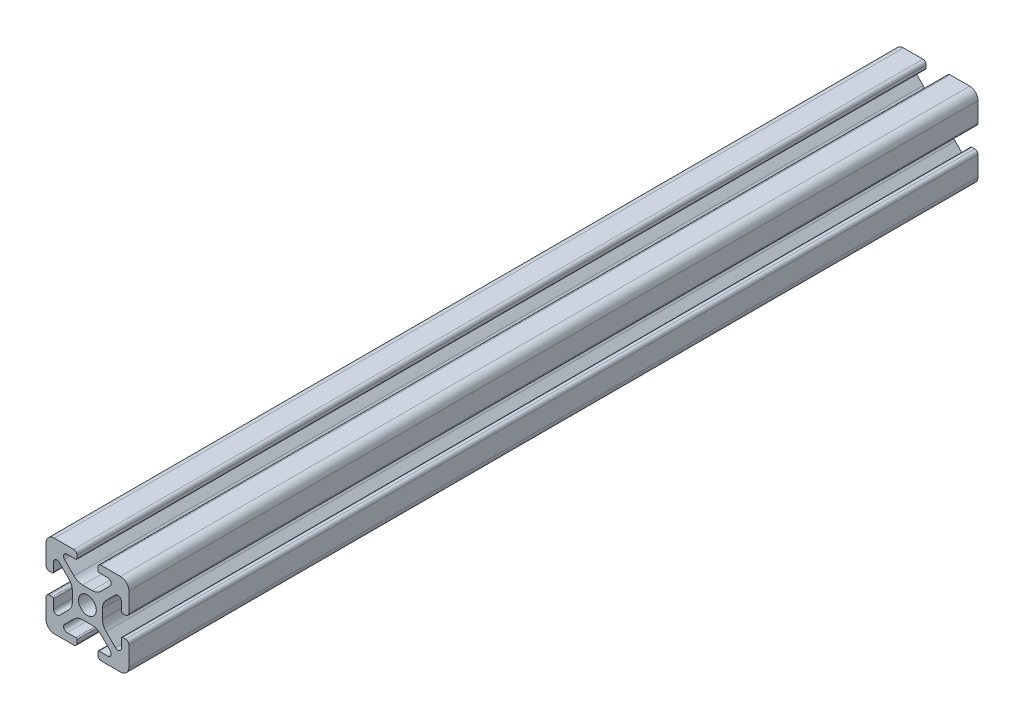
SolidWorks part; units mm, degrees
ref_plane "Front Plane" through (0, 0, 0) normal (0, 0, 1) x (1, 0, 0)
ref_plane "Top Plane" through (0, 0, 0) normal (0, 1, 0) x (1, 0, 0)
ref_plane "Right Plane" through (0, 0, 0) normal (1, 0, 0) x (0, 0, -1)
sketch "Sketch1" plane through (0, 0, 0) normal (0, 0, 1) x (1, 0, 0)
  line L2 (-9.9949, 7.9883) -> (-9.9949, 3.2893)
  line L3 (-7.9883, 9.9949) -> (-3.2893, 9.9949)
  line L4 (-2.5019, 9.2075) -> (-2.5019, 8.4963)
  line L5 (-2.8067, 8.1915) -> (-4.9149, 8.1915)
  line L6 (-5.5076, 6.7606) -> (-3.2528, 4.5058)
  line L7 (-6.7606, 5.5076) -> (-4.5058, 3.2528)
  line L8 (-8.1915, 4.9149) -> (-8.1915, 2.8067)
  line L9 (-8.4963, 2.5019) -> (-9.2075, 2.5019)
  line L11 (-1.1334, 3.6279) -> (1.1334, 3.6279)
  line L12 (-3.6279, 1.1334) -> (-3.6279, -1.1334)
  line L13 (8.4963, 2.5019) -> (9.2075, 2.5019)
  line L14 (8.1915, 4.9149) -> (8.1915, 2.8067)
  line L15 (9.9949, 7.9883) -> (9.9949, 3.2893)
  line L16 (7.9883, 9.9949) -> (3.2893, 9.9949)
  line L17 (2.5019, 9.2075) -> (2.5019, 8.4963)
  line L18 (2.8067, 8.1915) -> (4.9149, 8.1915)
  line L19 (3.6279, 1.1334) -> (3.6279, -1.1334)
  line L20 (5.5076, 6.7606) -> (3.2528, 4.5058)
  line L21 (6.7606, 5.5076) -> (4.5058, 3.2528)
  line L22 (-8.4963, -2.5019) -> (-9.2075, -2.5019)
  line L23 (-8.1915, -4.9149) -> (-8.1915, -2.8067)
  line L24 (-6.7606, -5.5076) -> (-4.5058, -3.2528)
  line L25 (-5.5076, -6.7606) -> (-3.2528, -4.5058)
  line L26 (-2.8067, -8.1915) -> (-4.9149, -8.1915)
  line L27 (-2.5019, -9.2075) -> (-2.5019, -8.4963)
  line L28 (-7.9883, -9.9949) -> (-3.2893, -9.9949)
  line L29 (-9.9949, -7.9883) -> (-9.9949, -3.2893)
  line L30 (9.9949, -7.9883) -> (9.9949, -3.2893)
  line L31 (7.9883, -9.9949) -> (3.2893, -9.9949)
  line L32 (2.5019, -9.2075) -> (2.5019, -8.4963)
  line L33 (2.8067, -8.1915) -> (4.9149, -8.1915)
  line L34 (5.5076, -6.7606) -> (3.2528, -4.5058)
  line L35 (6.7606, -5.5076) -> (4.5058, -3.2528)
  line L36 (8.1915, -4.9149) -> (8.1915, -2.8067)
  line L37 (8.4963, -2.5019) -> (9.2075, -2.5019)
  line L38 (-1.1334, -3.6279) -> (1.1334, -3.6279)
  circle A0 centre (0, 0) radius 2.1463
  arc A1 (-9.9949, 7.9883) -> (-7.9883, 9.9949) centre (-7.9883, 7.9883) cw
  arc A2 (-6.7606, 5.5076) -> (-8.1915, 4.9149) centre (-7.3533, 4.9149) ccw
  arc A3 (-4.9149, 8.1915) -> (-5.5076, 6.7606) centre (-4.9149, 7.3533) ccw
  arc A4 (-3.2893, 9.9949) -> (-2.5019, 9.2075) centre (-3.2893, 9.2075) cw
  arc A5 (-9.9949, 3.2893) -> (-9.2075, 2.5019) centre (-9.2075, 3.2893) ccw
  arc A6 (-8.1915, 2.8067) -> (-8.4963, 2.5019) centre (-8.4963, 2.8067) cw
  arc A7 (-2.5019, 8.4963) -> (-2.8067, 8.1915) centre (-2.8067, 8.4963) cw
  arc A8 (-1.1334, 3.6279) -> (-3.2528, 4.5058) centre (-1.1334, 6.6251) cw
  arc A9 (-3.6279, 1.1334) -> (-4.5058, 3.2528) centre (-6.6251, 1.1334) ccw
  arc A10 (8.1915, 2.8067) -> (8.4963, 2.5019) centre (8.4963, 2.8067) ccw
  arc A11 (9.9949, 3.2893) -> (9.2075, 2.5019) centre (9.2075, 3.2893) cw
  arc A12 (9.9949, 7.9883) -> (7.9883, 9.9949) centre (7.9883, 7.9883) ccw
  arc A13 (3.2893, 9.9949) -> (2.5019, 9.2075) centre (3.2893, 9.2075) ccw
  arc A14 (2.5019, 8.4963) -> (2.8067, 8.1915) centre (2.8067, 8.4963) ccw
  arc A15 (1.1334, 3.6279) -> (3.2528, 4.5058) centre (1.1334, 6.6251) ccw
  arc A16 (3.6279, 1.1334) -> (4.5058, 3.2528) centre (6.6251, 1.1334) cw
  arc A17 (6.7606, 5.5076) -> (8.1915, 4.9149) centre (7.3533, 4.9149) cw
  arc A18 (4.9149, 8.1915) -> (5.5076, 6.7606) centre (4.9149, 7.3533) cw
  arc A19 (-3.6279, -1.1334) -> (-4.5058, -3.2528) centre (-6.6251, -1.1334) cw
  arc A20 (-1.1334, -3.6279) -> (-3.2528, -4.5058) centre (-1.1334, -6.6251) ccw
  arc A21 (-2.5019, -8.4963) -> (-2.8067, -8.1915) centre (-2.8067, -8.4963) ccw
  arc A22 (-8.1915, -2.8067) -> (-8.4963, -2.5019) centre (-8.4963, -2.8067) ccw
  arc A23 (-9.9949, -3.2893) -> (-9.2075, -2.5019) centre (-9.2075, -3.2893) cw
  arc A24 (-3.2893, -9.9949) -> (-2.5019, -9.2075) centre (-3.2893, -9.2075) ccw
  arc A25 (-4.9149, -8.1915) -> (-5.5076, -6.7606) centre (-4.9149, -7.3533) cw
  arc A26 (-6.7606, -5.5076) -> (-8.1915, -4.9149) centre (-7.3533, -4.9149) cw
  arc A27 (-9.9949, -7.9883) -> (-7.9883, -9.9949) centre (-7.9883, -7.9883) ccw
  arc A28 (9.9949, -7.9883) -> (7.9883, -9.9949) centre (7.9883, -7.9883) cw
  arc A29 (6.7606, -5.5076) -> (8.1915, -4.9149) centre (7.3533, -4.9149) ccw
  arc A30 (4.9149, -8.1915) -> (5.5076, -6.7606) centre (4.9149, -7.3533) ccw
  arc A31 (3.2893, -9.9949) -> (2.5019, -9.2075) centre (3.2893, -9.2075) cw
  arc A32 (9.9949, -3.2893) -> (9.2075, -2.5019) centre (9.2075, -3.2893) ccw
  arc A33 (8.1915, -2.8067) -> (8.4963, -2.5019) centre (8.4963, -2.8067) cw
  arc A34 (2.5019, -8.4963) -> (2.8067, -8.1915) centre (2.8067, -8.4963) cw
  arc A35 (1.1334, -3.6279) -> (3.2528, -4.5058) centre (1.1334, -6.6251) cw
  arc A36 (3.6279, -1.1334) -> (4.5058, -3.2528) centre (6.6251, -1.1334) ccw
extrude "Boss-Extrude1" add sketch "Sketch1" along normal mid plane 205
